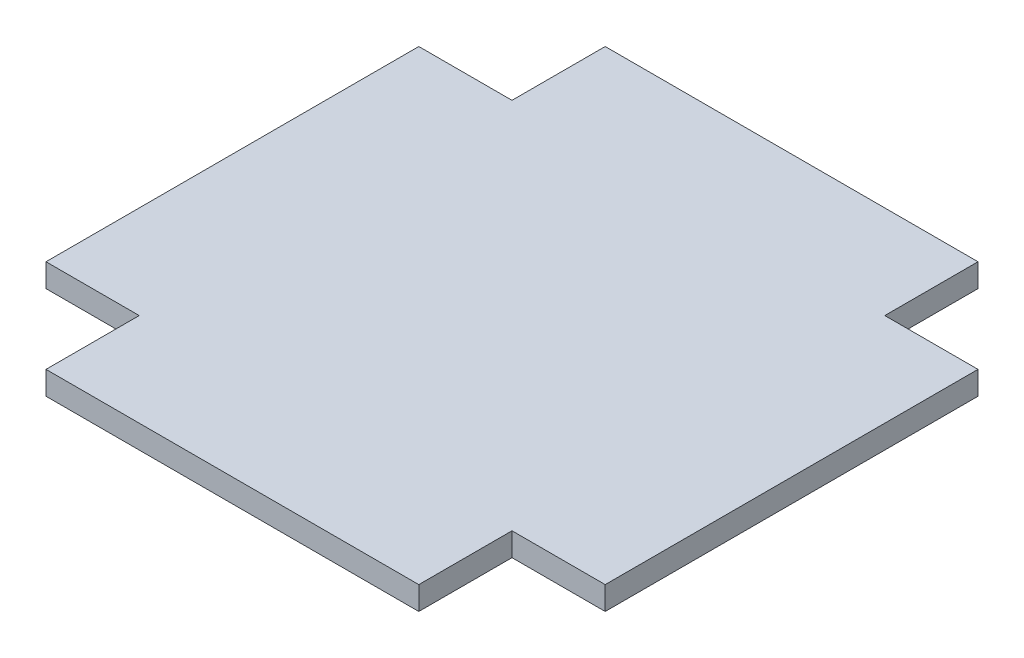
SolidWorks part; units mm, degrees
ref_plane "Front Plane" through (0, 0, 0) normal (0, 0, 1) x (1, 0, 0)
ref_plane "Top Plane" through (0, 0, 0) normal (0, 1, 0) x (1, 0, 0)
ref_plane "Right Plane" through (0, 0, 0) normal (1, 0, 0) x (0, 0, -1)
sketch "Sketch1" plane through (0, 0, 0) normal (0, 1, 0) x (1, 0, 0)
  line L0 (-20, 30) -> (-20, 20)
  line L1 (-20, 30) -> (20, 30)
  line L2 (-30, 20) -> (-30, -20)
  line L3 (-20, -30) -> (20, -30)
  line L4 (30, 20) -> (30, -20)
  line L5 (-30, 30) -> (30, -30) construction
  line L6 (-30, -30) -> (30, 30) construction
  line L7 (-20, 20) -> (-30, 20)
  line L8 (-30, -20) -> (-20, -20)
  line L9 (-20, -20) -> (-20, -30)
  line L10 (20, 30) -> (20, 20)
  line L11 (20, 20) -> (30, 20)
  line L12 (20, -30) -> (20, -20)
  line L13 (20, -20) -> (30, -20)
  point P0 (0, 0)
  dimension "D1" = 60
  dimension "D2" = 60
  dimension "D3" = 10
  dimension "D4" = 10
  dimension "D5" = 10
  dimension "D6" = 10
  dimension "D7" = 10
  dimension "D8" = 10
  dimension "D9" = 10
  dimension "D10" = 10
extrude "Boss-Extrude1" add sketch "Sketch1" along normal blind 2.5
